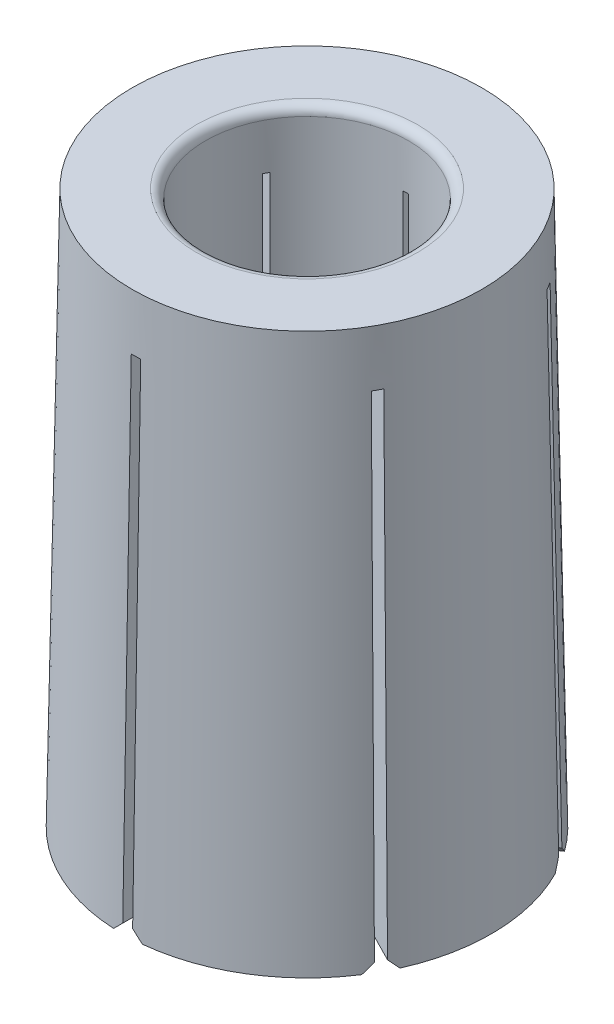
SolidWorks part; units mm, degrees
ref_plane "Front Plane" through (0, 0, 0) normal (0, 0, 1) x (1, 0, 0)
ref_plane "Top Plane" through (0, 0, 0) normal (0, 1, 0) x (1, 0, 0)
ref_plane "Right Plane" through (0, 0, 0) normal (1, 0, 0) x (0, 0, -1)
sketch "Sketch1" plane through (0, 0, 0) normal (0, 1, 0) x (1, 0, 0)
  circle A0 centre (0, 0) radius 3.5
  circle A1 centre (0, 0) radius 10
  dimension "D1" = 7
  dimension "D2" = 20
sketch "Sketch2" plane through (0, 0, 0) normal (0, 1, 0) x (1, 0, 0)
  circle A2 centre (0, 0) radius 3.5 construction
  circle A3 centre (0, 0) radius 10 construction
  circle A4 centre (0, 0) radius 3.5
  circle A5 centre (0, 0) radius 10
extrude "Boss-Extrude1" add sketch "Sketch2" along normal blind 30 draft 1
sketch "Sketch3" plane through (0, 30, 0) normal (0, 1, 0) x (1, 0, 0)
  circle A0 centre (0, 0) radius 5.5
  dimension "D1" = 11
extrude "Cut-Extrude1" cut sketch "Sketch3" against normal offset from surface (22 mm away) 8 up to face at (0, 0, 10)
chamfer "Chamfer1" distance 1 angle 45 1 edges at (0, 0, 3.5)
fillet "Fillet1" radius 0.5 1 edges at (0, 8, 3.6396)
sketch "Sketch4" plane through (0, 0, 0) normal (0, -1, 0) x (1, 0, 0)
  line L0 (0, 3.5) -> (0, 10)
  line L1 (0.1832, 3.4952) -> (0.5234, 9.9863)
  line L2 (0, 0) -> (0, 3.5) construction
  line L3 (0, 0) -> (0.1832, 3.4952) construction
  line L4 (3.0311, 1.75) -> (8.6603, 5)
  line L5 (3.1185, 1.589) -> (8.9101, 4.5399)
  line L6 (3.0311, -1.75) -> (8.6603, -5)
  line L7 (2.9353, -1.9062) -> (8.3867, -5.4464)
  line L8 (0, -3.5) -> (0, -10)
  line L9 (-0.1832, -3.4952) -> (-0.5234, -9.9863)
  line L10 (-3.0311, -1.75) -> (-8.6603, -5)
  line L11 (-3.1185, -1.589) -> (-8.9101, -4.5399)
  line L12 (-3.0311, 1.75) -> (-8.6603, 5)
  line L13 (-2.9353, 1.9062) -> (-8.3867, 5.4464)
  circle A0 centre (0, 0) radius 3.5 construction
  circle A1 centre (0, 0) radius 10 construction
  arc A2 (0.1832, 3.4952) -> (0, 3.5) centre (0, 0) ccw
  arc A3 (0.5234, 9.9863) -> (0, 10) centre (0, 0) ccw
  arc A4 (8.9101, 4.5399) -> (8.6603, 5) centre (0, 0) ccw
  arc A5 (3.1185, 1.589) -> (3.0311, 1.75) centre (0, 0) ccw
  arc A6 (8.3867, -5.4464) -> (8.6603, -5) centre (0, 0) ccw
  arc A7 (2.9353, -1.9062) -> (3.0311, -1.75) centre (0, 0) ccw
  arc A8 (-0.5234, -9.9863) -> (0, -10) centre (0, 0) ccw
  arc A9 (-0.1832, -3.4952) -> (0, -3.5) centre (0, 0) ccw
  arc A10 (-8.9101, -4.5399) -> (-8.6603, -5) centre (0, 0) ccw
  arc A11 (-3.1185, -1.589) -> (-3.0311, -1.75) centre (0, 0) ccw
  arc A12 (-8.3867, 5.4464) -> (-8.6603, 5) centre (0, 0) ccw
  arc A13 (-2.9353, 1.9062) -> (-3.0311, 1.75) centre (0, 0) ccw
  point P33 (0, 0)
  dimension "D1" = 3
  dimension "D2" = 2
extrude "Cut-Extrude2" cut sketch "Sketch4" against normal offset from surface (27 mm away) 3 up to face at (0, 30, 5.5)
chamfer "Chamfer2" distance 0.5 angle 45 12 edges at (-6.4522, 0, -3.2876) (-6.2713, 0, -3.6207) (-0.379, 0, -7.2316) (0, 0, -7.2415) (6.0732, 0, -3.944) (6.2713, 0, -3.6207) (6.4522, 0, 3.2876) (6.2713, 0, 3.6207) (0.379, 0, 7.2316) (0, 0, 7.2415) (-6.0732, 0, 3.944) (-6.2713, 0, 3.6207)
fillet "Fillet2" radius 0.5 1 edges at (0, 30, 5.5)
